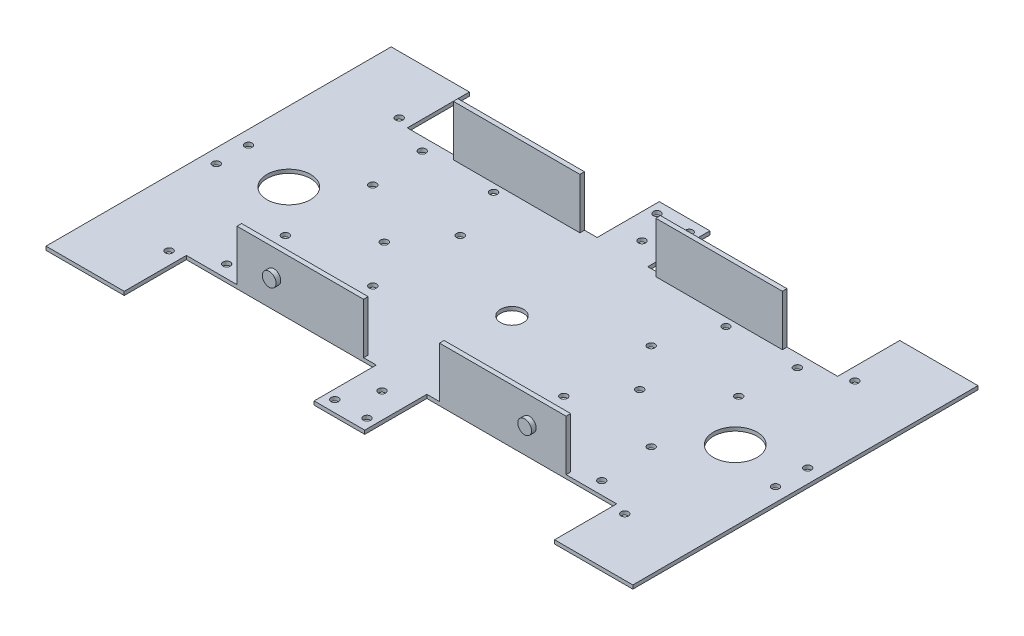
SolidWorks part; units mm, degrees
ref_plane "前视基准面" through (0, 0, 0) normal (0, 0, 1) x (1, 0, 0)
ref_plane "上视基准面" through (0, 0, 0) normal (0, 1, 0) x (1, 0, 0)
ref_plane "右视基准面" through (0, 0, 0) normal (1, 0, 0) x (0, 0, -1)
other "Configuration Table"
sketch "草图2" plane through (0, 0, 0) normal (0, 1, 0) x (1, 0, 0)
  line L0 (-11, 75) -> (11, 75)
  line L1 (-127.5, 75) -> (-93.5, 75)
  line L2 (-127.5, 75) -> (-127.5, -75)
  line L3 (-127.5, -75) -> (-93.5, -75)
  line L4 (127.5, 75) -> (127.5, -75)
  line L16 (-11, 75) -> (-11, 48)
  line L17 (-127.5, 75) -> (-93.5, 75)
  line L19 (0, 75) -> (0, -75) construction
  line L20 (-93.5, 75) -> (-93.5, 48)
  line L21 (-93.5, 48) -> (-11, 48)
  line L22 (93.5, 48) -> (11, 48)
  line L23 (11, 75) -> (11, 48)
  line L24 (93.5, 75) -> (93.5, 48)
  line L25 (-127.5, 0) -> (127.5, 0) construction
  line L26 (93.5, -75) -> (93.5, -48)
  line L27 (93.5, -48) -> (11, -48)
  line L28 (11, -75) -> (11, -48)
  line L29 (-11, -75) -> (-11, -48)
  line L30 (-93.5, -48) -> (-11, -48)
  line L31 (-93.5, -75) -> (-93.5, -48)
  line L32 (-11, 75) -> (11, 75)
  line L33 (93.5, 75) -> (127.5, 75)
  line L34 (-11, -75) -> (11, -75)
  line L35 (93.5, -75) -> (127.5, -75)
  circle A5 centre (0, 0) radius 5
  point P0 (0, 0)
  point P5 (0.2034, 0.1197)
  point P8 (-127.5, 0)
  point P9 (0.2034, 0.1197)
  point P12 (0.2034, 0.1197)
  point P14 (0, 75)
  point P17 (0.2034, 0.1197)
  point P26 (0, 0)
  dimension "D3" = 27
  dimension "D6" = 10
  dimension "D1" = 255
  dimension "D2" = 150
  dimension "D4" = 34
  dimension "D5" = 22
extrude "凸台-拉伸1" add sketch "草图2" along normal mid plane 1.6
sketch "草图3" plane through (0, 0.8, 0) normal (0, 1, 0) x (1, 0, 0)
  line L0 (-11, -48) -> (-16.5, -48)
  line L1 (0, 75) -> (0, -75) construction
  line L2 (-16.5, -48) -> (-71.5, -48)
  line L3 (-16.5, -48) -> (-16.5, -46)
  line L4 (-16.5, -46) -> (-71.5, -46)
  line L5 (-71.5, -48) -> (-71.5, -46)
  line L6 (-127.5, 0) -> (127.5, 0) construction
  line L7 (16.5, -46) -> (71.5, -46)
  line L8 (71.5, -48) -> (71.5, -46)
  line L9 (16.5, -48) -> (71.5, -48)
  line L10 (16.5, -48) -> (16.5, -46)
  line L11 (16.5, 48) -> (16.5, 46)
  line L12 (16.5, 48) -> (71.5, 48)
  line L13 (71.5, 48) -> (71.5, 46)
  line L14 (16.5, 46) -> (71.5, 46)
  line L15 (-16.5, 46) -> (-71.5, 46)
  line L16 (-71.5, 48) -> (-71.5, 46)
  line L17 (-16.5, 48) -> (-71.5, 48)
  line L18 (-16.5, 48) -> (-16.5, 46)
  line L20 (93.5, -48) -> (93.5, -75)
  line L21 (93.5, -75) -> (127.5, -75)
  line L22 (127.5, -75) -> (127.5, 75)
  line L23 (127.5, 75) -> (93.5, 75)
  line L24 (93.5, 75) -> (93.5, 48)
  line L25 (93.5, 48) -> (11, 48)
  line L26 (11, 48) -> (11, 75)
  line L27 (11, 75) -> (-11, 75)
  line L28 (-11, 75) -> (-11, 48)
  line L29 (-11, 48) -> (-93.5, 48)
  line L30 (-93.5, 48) -> (-93.5, 75)
  line L31 (-93.5, 75) -> (-127.5, 75)
  line L32 (-127.5, 75) -> (-127.5, -75)
  line L33 (-127.5, -75) -> (-93.5, -75)
  line L34 (-93.5, -75) -> (-93.5, -48)
  line L35 (-93.5, -48) -> (-11, -48)
  line L36 (-11, -48) -> (-11, -75)
  line L37 (-11, -75) -> (11, -75)
  line L38 (11, -75) -> (11, -48)
  line L39 (11, -48) -> (93.5, -48)
  line L40 (93.5, -48) -> (93.5, -75)
  line L41 (93.5, -75) -> (127.5, -75)
  line L42 (127.5, -75) -> (127.5, 75)
  line L43 (127.5, 75) -> (93.5, 75)
  line L44 (93.5, 75) -> (93.5, 48)
  line L45 (93.5, 48) -> (11, 48)
  line L46 (11, 48) -> (11, 75)
  line L47 (11, 75) -> (-11, 75)
  line L48 (-11, 75) -> (-11, 48)
  line L49 (-11, 48) -> (-93.5, 48)
  line L50 (-93.5, 48) -> (-93.5, 75)
  line L51 (-93.5, 75) -> (-127.5, 75)
  line L52 (-127.5, 75) -> (-127.5, -75)
  line L53 (-127.5, -75) -> (-93.5, -75)
  line L54 (-93.5, -75) -> (-93.5, -48)
  line L55 (-93.5, -48) -> (-11, -48)
  line L56 (-11, -48) -> (-11, -75)
  line L57 (-11, -75) -> (11, -75)
  line L58 (11, -75) -> (11, -48)
  line L59 (11, -48) -> (93.5, -48)
  point P20 (0, 0)
  dimension "D2" = 5.5
  dimension "D3" = 2
  dimension "D4" = 55
  dimension "D1" = 0
extrude "凸台-拉伸2" add sketch "草图3" along normal blind 22 contours L15 L16 L17 L18 | L12 L13 L14 L11 | L3 L4 L5 L2 | L7 L8 L9 L10
sketch "草图4" plane through (0, 0, 48) normal (0, 0, 1) x (1, 0, 0)
  line L0 (16.5, 11.8) -> (55.5, 11.8)
  line L1 (16.5, 22.8) -> (16.5, 0.8) construction
  line L2 (0, 0) -> (0, 26.5076)
  circle A0 centre (55.5, 11.8) radius 3
  circle A1 centre (-55.5, 11.8) radius 3
  dimension "D2" = 6
  dimension "D1" = 39
extrude "凸台-拉伸3" add sketch "草图4" along normal blind 2 contours A0 | A1
pattern_linear "阵列(线性)1" count 2 spacing 98 along (0, 0, -1) of "凸台-拉伸3"
sketch "草图5" plane through (0, -0.8, 0) normal (0, -1, 0) x (1, 0, 0)
  line L0 (0, -56.5) -> (0, 56.5) construction
  line L1 (0, 0) -> (0, 70) construction
  line L2 (7, 70) -> (-7, 70) construction
  line L3 (55.5, 0) -> (-55.5, 0) construction
  line L4 (99, -50) -> (-99, -50) construction
  line L5 (99, -50) -> (99, 50) construction
  line L6 (99, 50) -> (-99, 50) construction
  line L7 (-99, -50) -> (-99, 50) construction
  line L8 (99, -50) -> (-99, 50) construction
  line L9 (99, 50) -> (-99, -50) construction
  line L10 (-85.5, 80.6) -> (-85.5, 50) construction
  line L11 (-85.5, 80.6) -> (-85.5, 50)
  line L12 (-25.5, 50) -> (-25.5, 80.6) construction
  line L13 (-25.5, 50) -> (-25.5, 80.6)
  line L14 (-85.5, 50) -> (-25.5, 50)
  line L15 (-55.5, 50) -> (-55.5, 0)
  line L16 (55.5, 50) -> (55.5, 0)
  line L17 (-55.5, 0) -> (-81.5, 0)
  line L18 (-81.5, 42.5) -> (-81.5, -42.5) construction
  line L19 (-99, 0) -> (-97, 0)
  line L20 (-81.5, 0) -> (-121.5, 0) construction
  line L21 (-121.5, 0) -> (-121.5, -7) construction
  line L22 (-81.5, 0) -> (-79.5, 0) construction
  line L23 (-79.5, 0) -> (-79.5, 19) construction
  line L24 (-79.5, 19) -> (-41.5, 19) construction
  circle A0 centre (0, 56.5) radius 1.6
  circle A1 centre (7, 70) radius 1.6
  circle A2 centre (-7, 70) radius 1.6
  circle A3 centre (99, 50) radius 1.6
  circle A4 centre (-55.5, 0) radius 1.6
  circle A5 centre (-81.5, -42.5) radius 1.6
  circle A6 centre (-50.5, -42.5) radius 1.6
  circle A7 centre (-99, -50) radius 1.6
  circle A8 centre (-97, 0) radius 9.5
  circle A9 centre (-121.5, -7) radius 1.6
  circle A10 centre (55.5, 0) radius 1.6
  circle A11 centre (81.5, -42.5) radius 1.6
  circle A12 centre (50.5, -42.5) radius 1.6
  circle A13 centre (99, -50) radius 1.6
  circle A14 centre (121.5, -7) radius 1.6
  circle A15 centre (97, 0) radius 9.5
  circle A16 centre (7, -70) radius 1.6
  circle A17 centre (-7, -70) radius 1.6
  circle A18 centre (0, -56.5) radius 1.6
  circle A19 centre (50.5, 42.5) radius 1.6
  circle A20 centre (81.5, 42.5) radius 1.6
  circle A21 centre (99, 50) radius 1.6
  circle A22 centre (121.5, 7) radius 1.6
  circle A23 centre (-50.5, 42.5) radius 1.6
  circle A24 centre (-121.5, 7) radius 1.6
  circle A25 centre (-81.5, 42.5) radius 1.6
  circle A26 centre (-99, 50) radius 1.6
  circle A27 centre (-79.5, 19) radius 1.6
  circle A28 centre (-41.5, 19) radius 1.6
  circle A29 centre (-41.5, -19) radius 1.6
  circle A30 centre (-79.5, -19) radius 1.6
  circle A31 centre (41.5, 19) radius 1.6
  circle A32 centre (79.5, 19) radius 1.6
  circle A33 centre (41.5, -19) radius 1.6
  circle A34 centre (79.5, -19) radius 1.6
  point P5 (0, 0)
  point P12 (0, 70)
  point P22 (0, 0)
  point P33 (-81.5, 0)
  dimension "D2" = 3.2
  dimension "D4" = 3.2
  dimension "D5" = 3.2
  dimension "D8" = 3.2
  dimension "D10" = 3.2
  dimension "D12" = 40
  dimension "D13" = 3.2
  dimension "D18" = 3.2
  dimension "D1" = 113
  dimension "D3" = 70
  dimension "D6" = 85
  dimension "D7" = 26
  dimension "D9" = 31
  dimension "D11" = 2
  dimension "D14" = 7
  dimension "D15" = 2
  dimension "D16" = 19
  dimension "D17" = 38
extrude "切除-拉伸1" cut sketch "草图5" against normal blind 2
